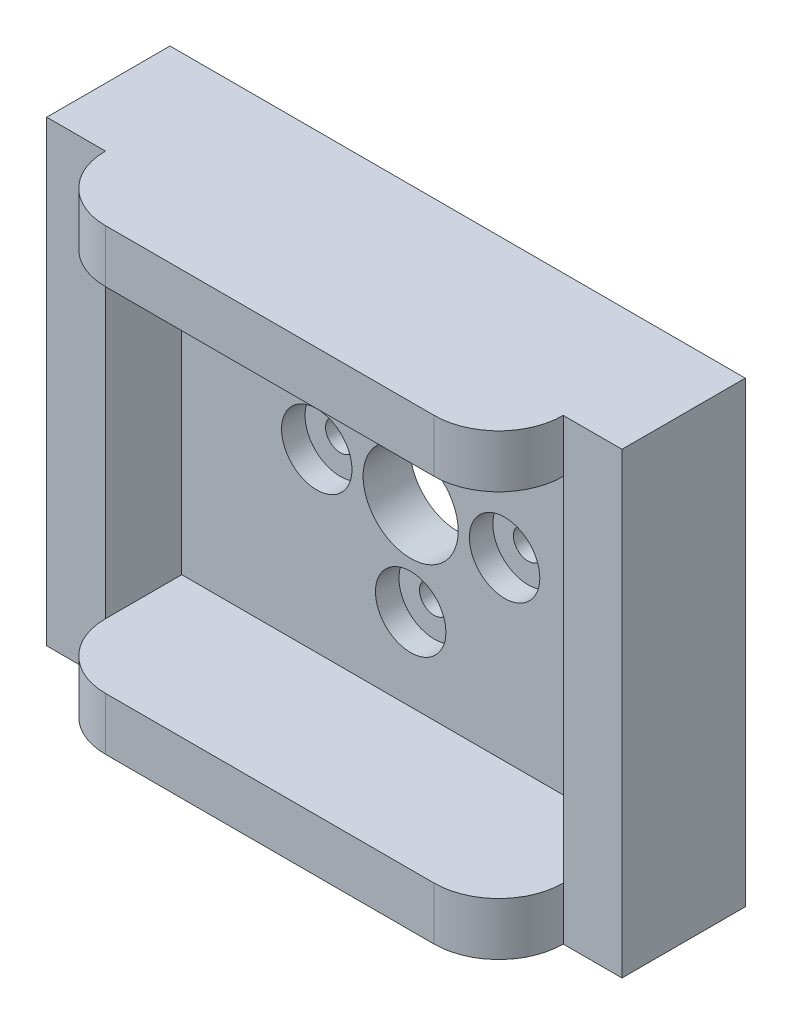
SolidWorks part; units mm, degrees
ref_plane "Front Plane" through (0, 0, 0) normal (0, 0, 1) x (1, 0, 0)
ref_plane "Top Plane" through (0, 0, 0) normal (0, 1, 0) x (1, 0, 0)
ref_plane "Right Plane" through (0, 0, 0) normal (1, 0, 0) x (0, 0, -1)
sketch "Sketch1" plane through (0, 0, 0) normal (0, 0, 1) x (1, 0, 0)
  line L5 (19.5, 0.8564) -> (-19.5, -22.8564) construction
  line L6 (19.5, -22.8564) -> (-19.5, 0.8564) construction
  line L7 (19.5, -22.8564) -> (-19.5, -22.8564)
  line L8 (19.5, -22.8564) -> (19.5, 0.8564)
  line L9 (19.5, 0.8564) -> (-19.5, 0.8564)
  line L10 (-19.5, -22.8564) -> (-19.5, 0.8564)
  line L11 (19.5, -22.8564) -> (-19.5, 0.8564) construction
  line L12 (19.5, 0.8564) -> (-19.5, -22.8564) construction
  arc A5 (1.25, -19) -> (-1.25, -19) centre (0, -19) ccw construction
  arc A6 (-1.25, -19) -> (1.25, -19) centre (0, -19) ccw construction
  arc A7 (1.25, -19) -> (-1.25, -19) centre (0, -19) ccw
  arc A8 (-1.25, -19) -> (1.25, -19) centre (0, -19) ccw
  arc A9 (-6.75, -11) -> (-9.25, -11) centre (-8, -11) ccw construction
  arc A10 (-6.75, -11) -> (-9.25, -11) centre (-8, -11) ccw
  arc A11 (-9.25, -11) -> (-6.75, -11) centre (-8, -11) ccw construction
  arc A12 (-9.25, -11) -> (-6.75, -11) centre (-8, -11) ccw
  arc A13 (1.25, -3) -> (-1.25, -3) centre (0, -3) ccw construction
  arc A14 (-1.25, -3) -> (1.25, -3) centre (0, -3) ccw construction
  arc A15 (1.25, -3) -> (-1.25, -3) centre (0, -3) ccw
  arc A16 (-1.25, -3) -> (1.25, -3) centre (0, -3) ccw
  arc A17 (9.25, -11) -> (6.75, -11) centre (8, -11) ccw construction
  arc A18 (6.75, -11) -> (9.25, -11) centre (8, -11) ccw construction
  arc A19 (9.25, -11) -> (6.75, -11) centre (8, -11) ccw
  arc A20 (6.75, -11) -> (9.25, -11) centre (8, -11) ccw
  point P0 (0, -11)
  point P8 (0, -11)
extrude "Boss-Extrude1" add sketch "Sketch1" along normal blind 2
sketch "Sketch9" plane through (0, 0, 2) normal (0, 0, 1) x (1, 0, 0)
  circle A0 centre (0, -11) radius 4.05
extrude "Cut-Extrude6" cut sketch "Sketch9" against normal blind 5
sketch "Sketch10" plane through (-19.5, 0, 0) normal (-1, 0, 0) x (0, 0, 1)
  line L0 (4.2, 3.5) -> (8.5, 3.5)
  line L1 (8.5, 3.5) -> (8.5, 0.5)
  line L2 (5, -3) -> (2, -3)
  line L3 (2, 0.8564) -> (2, -22.8564) construction
  line L4 (2, -3) -> (5, -3) construction
  line L5 (2, -3) -> (2, 0.8564)
  line L6 (2, 0.8564) -> (0, 0.8564)
  line L7 (0, 0.8564) -> (0, 3.5)
  line L8 (4.2, 3.5) -> (0, 3.5)
  line L9 (2, -11) -> (11.2, -11) construction
  line L10 (11.2, -17.2) -> (11.2, -4.8) construction
  line L11 (5, -19) -> (2, -19)
  line L12 (2, -19) -> (2, -22.8564)
  line L13 (2, -22.8564) -> (0, -22.8564)
  line L14 (0, -22.8564) -> (0, -25.5)
  line L15 (4.2, -25.5) -> (0, -25.5)
  line L16 (4.2, -25.5) -> (8.5, -25.5)
  line L17 (8.5, -25.5) -> (8.5, -22.5)
  arc A0 (5, -3) -> (8.5, 0.5) centre (5, 0.5) ccw construction
  arc A1 (5, -3) -> (8.5, 0.5) centre (5, 0.5) ccw
  circle A2 centre (5.25, 0.25) radius 1.25
  circle A3 centre (5.25, -22.25) radius 1.25
  arc A4 (5, -19) -> (8.5, -22.5) centre (5, -22.5) cw
  dimension "D1" = 2.5
extrude "Boss-Extrude5" add sketch "Sketch10" against normal up to surface (5.5 mm away)
sketch "Sketch11" plane through (-19.5, 0, 0) normal (-1, 0, 0) x (0, 0, 1)
  line L0 (3.2, -11) -> (11.2, -11) construction
  line L1 (3.2, -4.8) -> (3.2, -17.2) construction
  line L2 (11.2, -17.2) -> (11.2, -4.8) construction
  circle A0 centre (5.25, 0.25) radius 2.5
  circle A1 centre (5.25, -22.25) radius 2.5
  dimension "D1" = 5
extrude "Cut-Extrude7" cut sketch "Sketch11" against normal blind 5
sketch "Sketch12" plane through (19.5, 0, 0) normal (1, 0, 0) x (0, 0, -1)
  line L4 (-5, -3) -> (-2, -3)
  line L6 (-5, -3) -> (-2, -3)
  line L8 (-2, -3) -> (-2, -19)
  line L12 (0, -25.5) -> (0, 3.5)
  line L14 (-8.5, 3.5) -> (-8.5, 0.5)
  line L15 (-8.5, 3.5) -> (-8.5, 0.5)
  line L16 (-2, -3) -> (-2, -19)
  line L20 (0, -25.5) -> (0, 3.5)
  line L24 (0, 3.5) -> (-8.5, 3.5)
  line L25 (0, 3.5) -> (-8.5, 3.5)
  line L26 (-8.5, -25.5) -> (0, -25.5)
  line L27 (-8.5, -25.5) -> (0, -25.5)
  line L28 (-8.5, -22.5) -> (-8.5, -25.5)
  line L29 (-8.5, -22.5) -> (-8.5, -25.5)
  line L30 (-2, -19) -> (-5, -19)
  line L31 (-2, -19) -> (-5, -19)
  circle A0 centre (-5.25, -22.25) radius 2.5 construction
  circle A1 centre (-5.25, 0.25) radius 2.5 construction
  circle A6 centre (-5.25, -22.25) radius 2.5
  circle A7 centre (-5.25, 0.25) radius 2.5
  arc A8 (-8.5, 0.5) -> (-5, -3) centre (-5, 0.5) ccw
  arc A9 (-8.5, 0.5) -> (-5, -3) centre (-5, 0.5) ccw
  arc A10 (-5, -19) -> (-8.5, -22.5) centre (-5, -22.5) ccw
  arc A11 (-5, -19) -> (-8.5, -22.5) centre (-5, -22.5) ccw
  dimension "D1" = 0
extrude "Boss-Extrude6" add sketch "Sketch12" against normal up to surface (5.5 mm away) contours L20 L25 L15 A9 L6 L16 L31 A11 L29 L27 | A6 | A7
sketch "Sketch13" plane through (14, 0, 0) normal (-1, 0, 0) x (0, 0, 1)
  line L0 (0, 3.5) -> (4.2, 3.5)
  line L1 (0, 3.5) -> (8.5, 3.5) construction
  line L2 (4.2, 3.5) -> (2, 1.3) construction
  line L3 (4.2, 3.5) -> (2, 1.3)
  line L4 (2, 1.3) -> (2, 0.8564)
  line L5 (2, 0.8564) -> (0, 0.8564)
  line L6 (0, 0.8564) -> (0, 3.5)
  line L7 (3.2, -11) -> (11.2, -11) construction
  line L8 (3.2, -4.8) -> (3.2, -17.2) construction
  line L9 (11.2, -17.2) -> (11.2, -4.8) construction
  line L10 (2, -22.8564) -> (0, -22.8564)
  line L11 (2, -23.3) -> (2, -22.8564)
  line L12 (4.2, -25.5) -> (2, -23.3)
  line L13 (0, -25.5) -> (4.2, -25.5)
  line L14 (0, -22.8564) -> (0, -25.5)
extrude "Boss-Extrude7" add sketch "Sketch13" along normal up to surface (28 mm away) up to face at (-14, 0.3554, 3.8178)
sketch "Sketch14" plane through (0, 0, 0) normal (0, 0, -1) x (-1, 0, 0)
  line L4 (19.5, 3.5) -> (-19.5, 3.5)
  line L5 (-19.5, 3.5) -> (-19.5, -25.5)
  line L6 (-19.5, -25.5) -> (19.5, -25.5)
  line L7 (19.5, -25.5) -> (19.5, 3.5)
  line L8 (19.5, 3.5) -> (-19.5, 3.5)
  line L9 (-19.5, 3.5) -> (-19.5, -25.5)
  line L10 (-19.5, -25.5) -> (19.5, -25.5)
  line L11 (19.5, -25.5) -> (19.5, 3.5)
  circle A0 centre (0, -19) radius 1.25 construction
  circle A1 centre (8, -11) radius 1.25 construction
  circle A2 centre (0, -3) radius 1.25 construction
  circle A3 centre (0, -11) radius 4.05 construction
  circle A4 centre (-8, -11) radius 1.25 construction
  circle A5 centre (0, -19) radius 1.25
  circle A6 centre (8, -11) radius 1.25
  circle A7 centre (0, -3) radius 1.25
  circle A8 centre (0, -11) radius 4.05
  circle A9 centre (-8, -11) radius 1.25
  dimension "D1" = 0
extrude "Boss-Extrude8" add sketch "Sketch14" along normal blind 2
sketch "Sketch15" plane through (0, 0, 2) normal (0, 0, 1) x (1, 0, 0)
  circle A0 centre (0, -3) radius 3
  circle A1 centre (8, -11) radius 3
  circle A2 centre (0, -19) radius 3
  circle A3 centre (-8, -11) radius 3
  point P12 (0, -11)
  dimension "D1" = 6
  dimension "D2" = 4
extrude "Cut-Extrude8" cut sketch "Sketch15" against normal blind 2
sketch "Sketch16" plane through (0, 3.5, 0) normal (0, 1, 0) x (1, 0, 0)
  line L0 (14, -14) -> (-14, -14)
  line L8 (-14, -8.5) -> (-14, -4.2)
  line L9 (-14, -4.2) -> (14, -4.2)
  line L10 (14, -4.2) -> (14, -8.5)
  line L11 (14, -8.5) -> (19.5, -8.5)
  line L12 (19.5, -8.5) -> (19.5, 2)
  line L13 (19.5, 2) -> (-19.5, 2)
  line L14 (-19.5, 2) -> (-19.5, -8.5)
  line L15 (-19.5, -8.5) -> (-14, -8.5)
  line L16 (-14, -4.4928) -> (-14, -4.2)
  line L20 (19.5, -8.5) -> (19.5, 2)
  line L21 (19.5, 2) -> (-19.5, 2)
  line L22 (-19.5, 2) -> (-19.5, -8.5)
  arc A0 (14, -14) -> (19.5, -8.5) centre (14, -8.5) ccw
  arc A1 (-19.5, -8.5) -> (-14, -14) centre (-14, -8.5) ccw
  line M12 (-14, -8.5) -> (-14, -4.2)
  line M13 (-14, -4.2) -> (14, -4.2)
  line M14 (14, -4.2) -> (14, -8.5)
  line M15 (14, -8.5) -> (19.5, -8.5)
  line M16 (19.5, -8.5) -> (19.5, 2)
  line M17 (19.5, 2) -> (-19.5, 2)
  line M18 (-19.5, 2) -> (-19.5, -8.5)
  line M19 (-19.5, -8.5) -> (-14, -8.5)
  dimension "D1" = 0
extrude "Boss-Extrude9" add sketch "Sketch16" along normal blind 5 contours A1 L0 A0 M19 M15 M14 M13 M12 | M19 M12 M13 M14 M15 M16 M17 M18
sketch "Sketch17" plane through (0, -25.5, 0) normal (0, -1, 0) x (1, 0, 0)
  line L4 (19.5, -2) -> (19.5, 8.5)
  line L5 (-19.5, -2) -> (19.5, -2)
  line L6 (-19.5, 8.5) -> (-19.5, -2)
  line L7 (14, 14) -> (-14, 14)
  line L8 (19.5, -2) -> (19.5, 8.5)
  line L9 (-19.5, -2) -> (19.5, -2)
  line L10 (-19.5, 8.5) -> (-19.5, -2)
  line L11 (14, 14) -> (-14, 14)
  arc A2 (19.5, 8.5) -> (14, 14) centre (14, 8.5) ccw
  arc A3 (-14, 14) -> (-19.5, 8.5) centre (-14, 8.5) ccw
  arc A4 (19.5, 8.5) -> (14, 14) centre (14, 8.5) ccw
  arc A5 (-14, 14) -> (-19.5, 8.5) centre (-14, 8.5) ccw
  dimension "D1" = 0
extrude "Boss-Extrude10" add sketch "Sketch17" along normal blind 5
sketch "Sketch18" plane through (0, 0, 14) normal (0, 0, 1) x (1, 0, 0)
  line L0 (0, -23.3) -> (0, 1.3) construction
  line L1 (-14, -23.3) -> (14, -23.3) construction
  line L2 (-14, 1.3) -> (14, 1.3) construction
  line L3 (-19.5, 0.5) -> (-19.5, 3.5) construction
  line L4 (19.5, -26) -> (-19.5, -26)
  line L5 (19.5, -26) -> (19.5, 4)
  line L6 (19.5, 4) -> (-19.5, 4)
  line L7 (-19.5, -26) -> (-19.5, 4)
  line L8 (19.5, -26) -> (-19.5, 4) construction
  line L9 (19.5, 4) -> (-19.5, -26) construction
  point P6 (0, -11)
  dimension "D1" = 30
extrude "Cut-Extrude9" cut sketch "Sketch18" against normal up to surface (12 mm away) up to face at (3, -3, 2)
sketch "Sketch19" plane through (-19.5, 0, 0) normal (-1, 0, 0) x (0, 0, 1)
  line L1 (-2, 8.5) -> (8.5, 8.5)
  line L2 (-2, 8.5) -> (-2, -30.5)
  line L3 (-2, -30.5) -> (8.5, -30.5)
  line L4 (8.5, 8.5) -> (8.5, -30.5)
extrude "Boss-Extrude11" add sketch "Sketch19" along normal blind 5
sketch "Sketch20" plane through (19.5, 0, 0) normal (1, 0, 0) x (0, 0, -1)
  line L1 (2, 8.5) -> (-8.5, 8.5)
  line L2 (2, 8.5) -> (2, -30.5)
  line L3 (2, -30.5) -> (-8.5, -30.5)
  line L4 (-8.5, 8.5) -> (-8.5, -30.5)
extrude "Boss-Extrude12" add sketch "Sketch20" along normal blind 5
